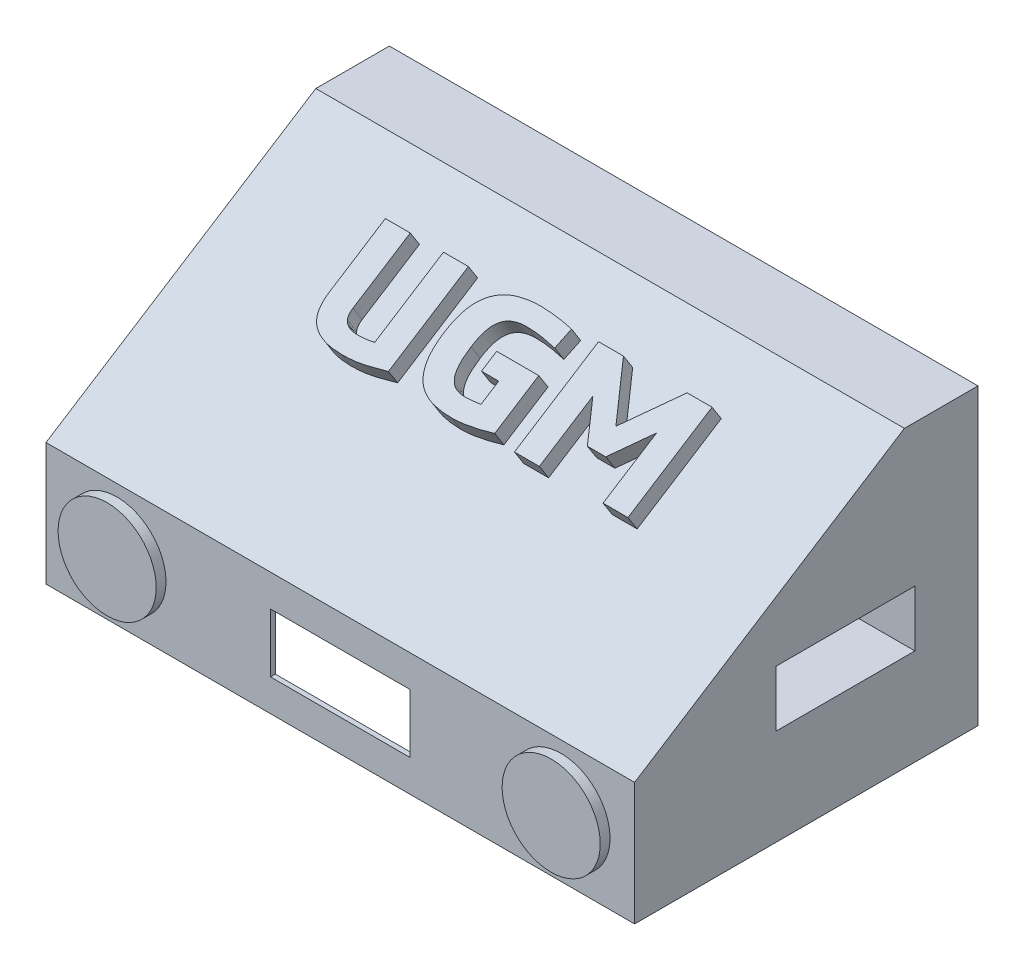
SolidWorks part; units mm, degrees
ref_plane "Front Plane" through (0, 0, 0) normal (0, 0, 1) x (1, 0, 0)
ref_plane "Top Plane" through (0, 0, 0) normal (0, 1, 0) x (1, 0, 0)
ref_plane "Right Plane" through (0, 0, 0) normal (1, 0, 0) x (0, 0, -1)
sketch "Sketch2" plane through (0, 0, 0) normal (1, 0, 0) x (0, 0, -1)
  line L0 (0, 0) -> (-70, 0)
  line L1 (0, 0) -> (0, 60)
  line L2 (0, 60) -> (-15, 60)
  line L4 (-70, 0) -> (-70, 25)
  line L5 (-70, 25) -> (-15, 60)
  line L6 (-41.1666, 31.0884) -> (-12.8597, 31.0884)
  line L7 (-12.8597, 31.0884) -> (-12.8597, 19.6344)
  line L8 (-12.8597, 19.6344) -> (-41.1666, 19.6344)
  line L9 (-41.1666, 19.6344) -> (-41.1666, 31.0884)
  dimension "D1" = 70
  dimension "D2" = 60
  dimension "D3" = 15
  dimension "D4" = 25
extrude "Boss-Extrude1" add sketch "Sketch2" along normal blind 120
shell "Shell1" thickness 1
sketch "Sketch3" plane through (0, 0, 70) normal (0, 0, 1) x (1, 0, 0)
  circle A0 centre (14.4605, 12.6224) radius 10
  circle A1 centre (104.9848, 12.6224) radius 10
extrude "Boss-Extrude3" add sketch "Sketch3" along normal blind 2
sketch "Sketch4" plane through (0, 49.5, 31.5) normal (0, 0.8437, 0.5369) x (1, 0, 0)
  line L0 (0, -13.0384) -> (120, -13.0384) construction
  line L1 (0, 19.5576) -> (0, -45.6344) construction
  line L2 (120, 19.5576) -> (120, -45.6344) construction
  text T0 "UGM" font "3ds" height in points 72
extrude "Boss-Extrude4" add sketch "Sketch4" along normal blind 3.5
sketch "Sketch5" plane through (0, 0, 70) normal (0, 0, 1) x (1, 0, 0)
  line L0 (60, 25) -> (60, 0) construction
  line L1 (120, 25) -> (0, 25) construction
  line L2 (120, 0) -> (0, 0) construction
  line L4 (74.25, 6.5) -> (45.75, 6.5)
  line L5 (74.25, 6.5) -> (74.25, 18.5)
  line L6 (74.25, 18.5) -> (45.75, 18.5)
  line L7 (45.75, 6.5) -> (45.75, 18.5)
  line L8 (74.25, 6.5) -> (45.75, 18.5) construction
  line L9 (74.25, 18.5) -> (45.75, 6.5) construction
  point P6 (60, 12.5)
  dimension "D1" = 28.5
  dimension "D2" = 12
extrude "Cut-Extrude1" cut sketch "Sketch5" against normal blind 3.5
